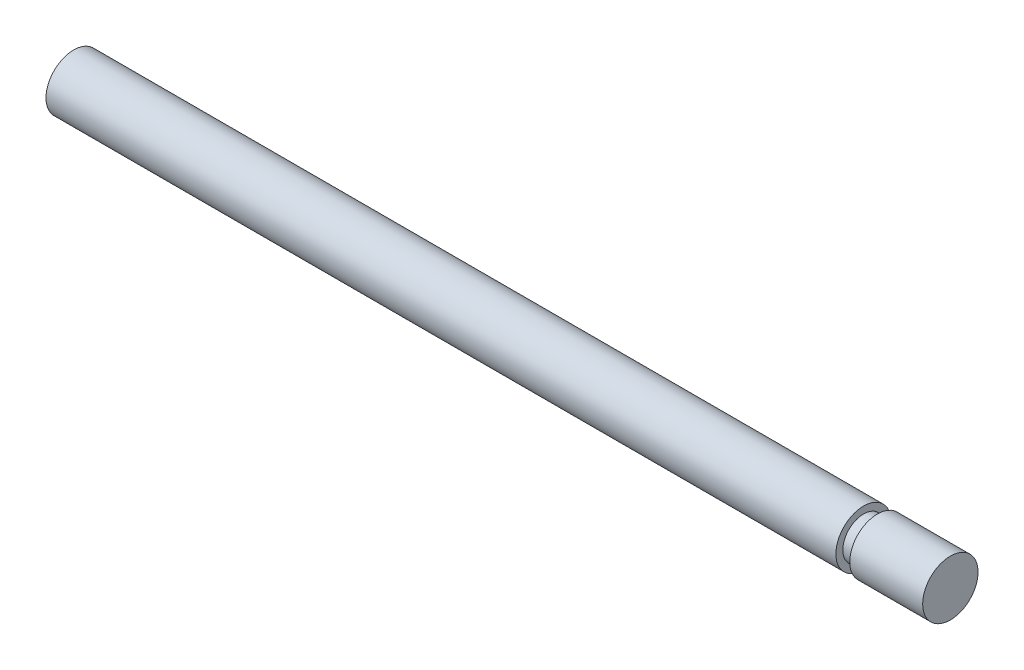
SolidWorks part; units mm, degrees
ref_plane "Front Plane" through (0, 0, 0) normal (0, 0, 1) x (1, 0, 0)
ref_plane "Top Plane" through (0, 0, 0) normal (0, 1, 0) x (1, 0, 0)
ref_plane "Right Plane" through (0, 0, 0) normal (1, 0, 0) x (0, 0, -1)
sketch "Sketch1" plane through (0, 0, 0) normal (0, 0, 1) x (1, 0, 0)
  line L0 (0, 0) -> (0, 50)
  line L1 (0, 0) -> (1583, 0)
  line L2 (1583, 0) -> (1583, 50)
  line L3 (1583, 50) -> (1451.3, 50)
  line L4 (1451.3, 50) -> (1451.3, 37.5)
  line L5 (1451.3, 37.5) -> (1426.3, 37.5)
  line L6 (1426.3, 37.5) -> (1426.3, 50)
  line L7 (1426.3, 50) -> (0, 50)
  dimension "D1" = 50
  dimension "D2" = 1583
  dimension "D3" = 131.7
  dimension "D4" = 12.5
  dimension "D5" = 25
revolve "Revolve1" add sketch "Sketch1" angle 360 about L1
